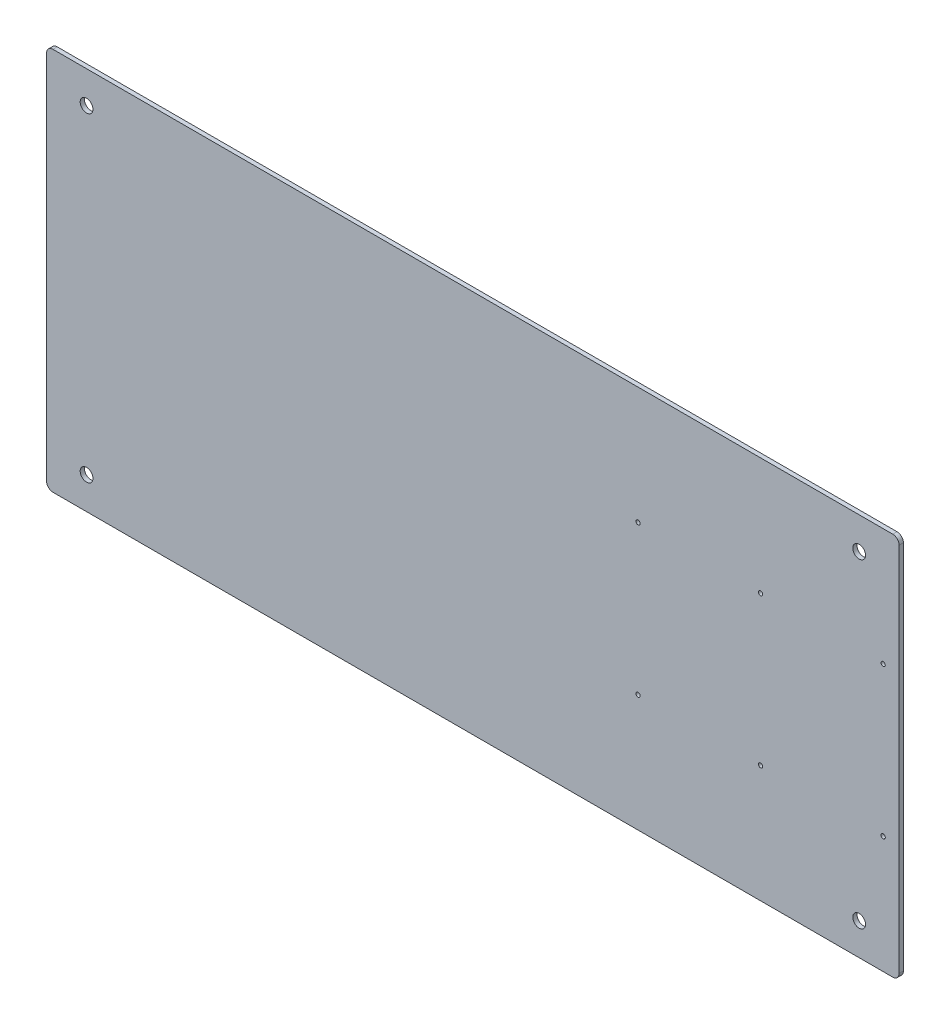
SolidWorks part; units mm, degrees
material "PMMA"
ref_plane "前视基准面" through (0, 0, 0) normal (0, 0, 1) x (1, 0, 0)
ref_plane "上视基准面" through (0, 0, 0) normal (0, 1, 0) x (1, 0, 0)
ref_plane "右视基准面" through (0, 0, 0) normal (1, 0, 0) x (0, 0, -1)
other "Configuration Table"
sketch "草图1" plane through (0, 0, 0) normal (0, 0, 1) x (1, 0, 0)
  line L1 (-400, -180) -> (400, -180)
  line L2 (-400, -180) -> (-400, 180)
  line L3 (-400, 180) -> (400, 180)
  line L4 (400, -180) -> (400, 180)
  line L5 (-400, -180) -> (400, 180) construction
  line L6 (-400, 180) -> (400, -180) construction
  line L7 (-362.5, 150) -> (362.5, 150) construction
  line L8 (-362.5, 150) -> (-362.5, -150) construction
  line L9 (-362.5, -150) -> (362.5, -150) construction
  line L10 (362.5, 150) -> (362.5, -150) construction
  line L11 (-362.5, 150) -> (362.5, -150) construction
  line L12 (-362.5, -150) -> (362.5, 150) construction
  line L13 (155, -70) -> (385, -70) construction
  line L14 (155, -70) -> (155, 70) construction
  line L15 (155, 70) -> (385, 70) construction
  line L16 (385, -70) -> (385, 70) construction
  line L17 (155, -70) -> (385, 70) construction
  line L18 (155, 70) -> (385, -70) construction
  circle A0 centre (-362.5, 150) radius 6
  circle A1 centre (-362.5, -150) radius 6
  circle A2 centre (362.5, -150) radius 6
  circle A3 centre (362.5, 150) radius 6
  circle A4 centre (155, 70) radius 2
  circle A5 centre (270, 70) radius 2
  circle A6 centre (385, 70) radius 2
  circle A7 centre (385, -70) radius 2
  circle A8 centre (270, -70) radius 2
  circle A9 centre (155, -70) radius 2
  point P0 (0, 0)
  point P10 (0, 0)
  point P15 (270, 0)
  dimension "D5" = 12
  dimension "D8" = 4
  dimension "D1" = 800
  dimension "D2" = 360
  dimension "D3" = 725
  dimension "D4" = 300
  dimension "D6" = 230
  dimension "D7" = 140
  dimension "D9" = 15
extrude "凸台-拉伸1" add sketch "草图1" along normal blind 4
fillet "圆角1" radius 6 4 edges at (-400, -180, 2) (400, -180, 2) (400, 180, 2) (-400, 180, 2)
